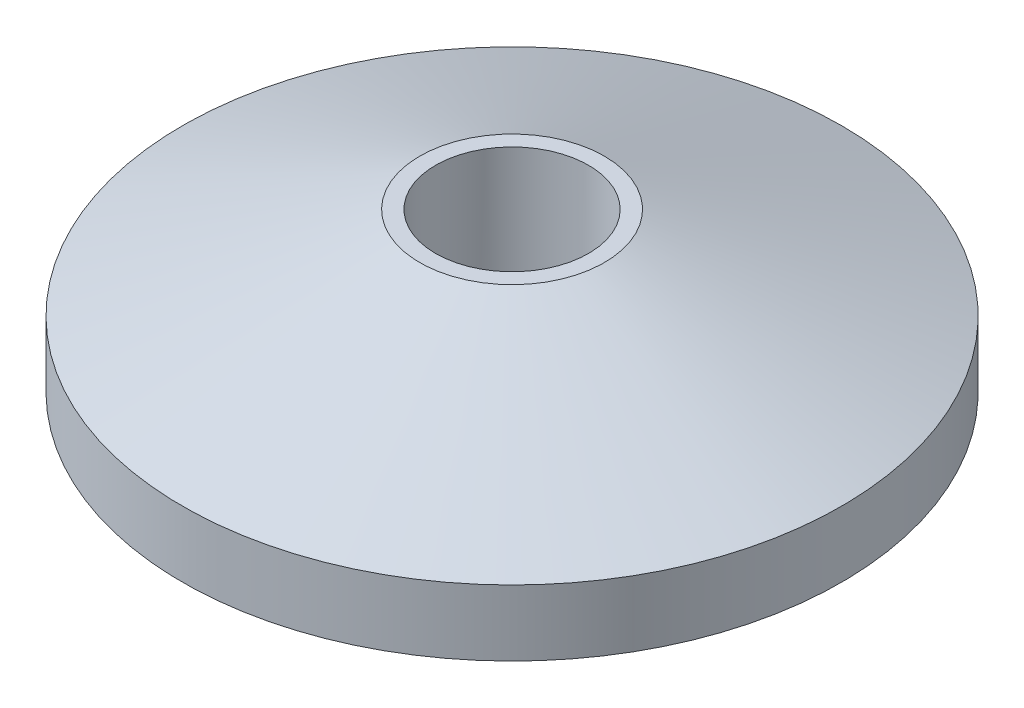
SolidWorks part; units mm, degrees
ref_plane "Front Plane" through (0, 0, 0) normal (0, 0, 1) x (1, 0, 0)
ref_plane "Top Plane" through (0, 0, 0) normal (0, 1, 0) x (1, 0, 0)
ref_plane "Right Plane" through (0, 0, 0) normal (1, 0, 0) x (0, 0, -1)
sketch "Sketch1" plane through (0, 0, 0) normal (1, 0, 0) x (0, 0, -1)
  line L0 (0, 0) -> (12.5, 0)
  line L1 (12.5, 0) -> (12.5, 2.5)
  line L2 (12.5, 2.5) -> (3.5, 6)
  line L3 (3.5, 6) -> (0, 6)
  line L4 (0, 6) -> (0, 0)
  line L5 (0, 6) -> (0, 12.905) construction
  dimension "D1" = 7
  dimension "D2" = 25
  dimension "D3" = 2.5
  dimension "D4" = 6
revolve "Revolve1" add sketch "Sketch1" angle 360 about L5
sketch "Sketch2" plane through (0, 6, 0) normal (0, 1, 0) x (1, 0, 0)
  circle A0 centre (0, 0) radius 2.9
  dimension "D1" = 5.8
extrude "Cut-Extrude1" cut sketch "Sketch2" against normal offset from surface (5 mm away) 1 up to face at (0, 0, -12.5)
